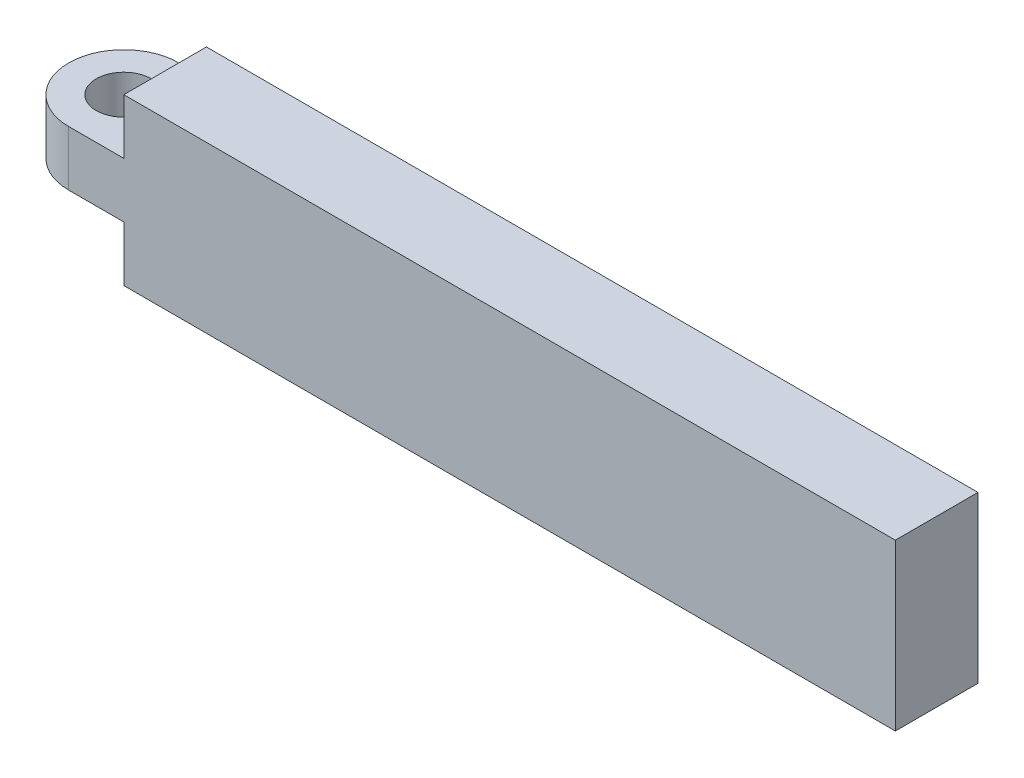
SolidWorks part; units mm, degrees
ref_plane "Front Plane" through (0, 0, 0) normal (0, 0, 1) x (1, 0, 0)
ref_plane "Top Plane" through (0, 0, 0) normal (0, 1, 0) x (1, 0, 0)
ref_plane "Right Plane" through (0, 0, 0) normal (1, 0, 0) x (0, 0, -1)
sketch "Sketch1" plane through (0, 0, 0) normal (0, 1, 0) x (1, 0, 0)
  line L1 (-7, 1) -> (7, 1)
  line L2 (-7, 1) -> (-7, -1)
  line L3 (-7, -1) -> (7, -1)
  line L4 (7, 1) -> (7, -1)
  line L5 (-7, 1) -> (7, -1) construction
  line L6 (-7, -1) -> (7, 1) construction
  point P0 (0, 0)
  dimension "D1" = 14
  dimension "D2" = 2
extrude "Boss-Extrude1" add sketch "Sketch1" along normal blind 3
chamfer "Chamfer1" distance 0.5 angle 45 3 edges at (0, 0, -1) (7, 1.5, -1) (0, 3, -1)
sketch "Sketch2" plane through (-7, 0, 0) normal (-1, 0, 0) x (0, 0, 1)
  line L0 (1, 3) -> (1, 0) construction
  line L1 (-1, 1) -> (1, 1)
  line L2 (-1, 1) -> (-1, 2)
  line L3 (-1, 2) -> (1, 2)
  line L4 (1, 1) -> (1, 2)
  line L5 (-1, 1) -> (1, 2) construction
  line L6 (-1, 2) -> (1, 1) construction
  point P0 (0, 1.5)
  point P8 (1, 1.5)
  dimension "D1" = 1
extrude "Boss-Extrude2" add sketch "Sketch2" along normal blind 2
sketch "Sketch3" plane through (0, 2, 0) normal (0, 1, 0) x (1, 0, 0)
  line L0 (-9, -1) -> (-7, -1) construction
  line L1 (-9, -1) -> (-9, 1) construction
  line L6 (-7, -1) -> (-7, 1)
  line L7 (-7, 1) -> (-9, 1)
  line L8 (-9, 1) -> (-9, -1)
  line L9 (-9, -1) -> (-7, -1)
  line L10 (-7, -1) -> (-7, 1)
  line L11 (-7, 1) -> (-9, 1)
  line L12 (-9, 1) -> (-9, -1)
  line L13 (-9, -1) -> (-7, -1)
  circle A0 centre (-8, 0) radius 1
  circle A1 centre (-8, 0) radius 0.5
  point P4 (-8, -1)
  point P7 (-9, 0)
  line M7 (-9, 1) -> (-9, -1)
  line M8 (-9, -1) -> (-7, -1)
  dimension "D1" = 2
  dimension "D2" = 0.5
  dimension "D3" = 0
extrude "Cut-Extrude1" cut sketch "Sketch3" against normal blind 2 contours A1 | A0 L11 M7 | A0 L12 M8
